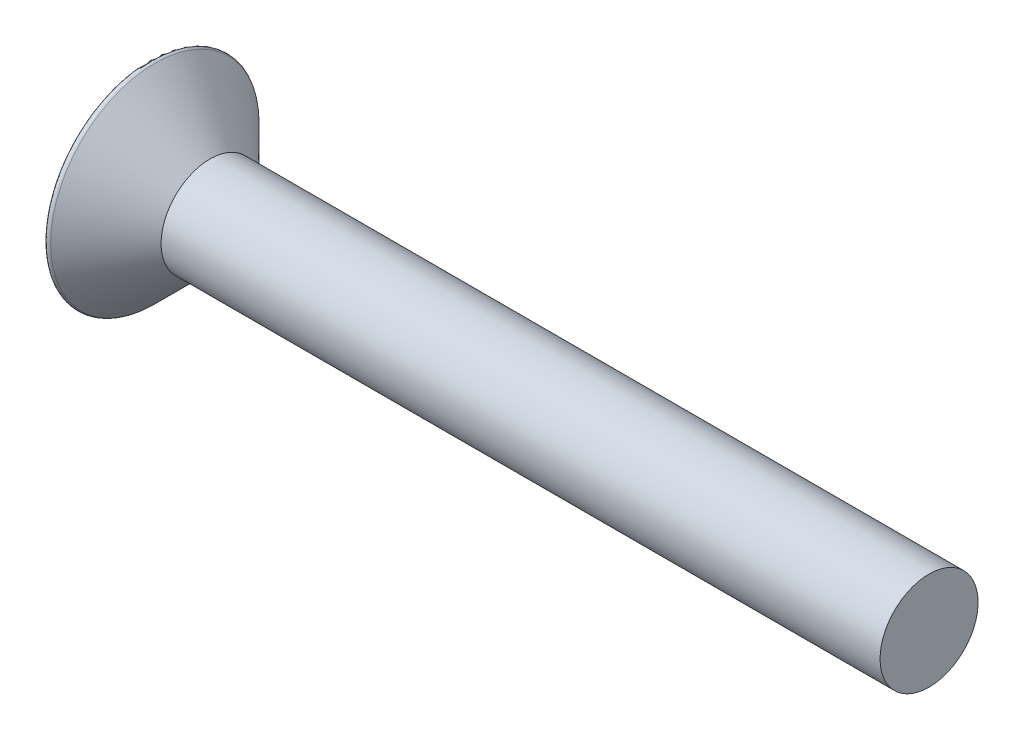
SolidWorks part; units mm, degrees
ref_plane "Plan de face" through (0, 0, 0) normal (0, 0, 1) x (1, 0, 0)
ref_plane "Plan de dessus" through (0, 0, 0) normal (0, 1, 0) x (1, 0, 0)
ref_plane "Plan de droite" through (0, 0, 0) normal (1, 0, 0) x (0, 0, -1)
sketch "Esquisse1" plane through (0, 0, 0) normal (0, 0, 1) x (1, 0, 0)
  line L0 (0, 0) -> (23.86, 0) construction
  line L1 (0, 0) -> (0, 3.36)
  line L2 (0, 3.36) -> (1.86, 1.5)
  line L3 (1.86, 1.5) -> (23.86, 1.5)
  line L4 (23.86, 1.5) -> (23.86, 0)
  line L5 (0, 0) -> (23.86, 0)
  dimension "D1" = 3.36
  dimension "D2" = 1.86
  dimension "D3" = 45
  dimension "D4" = 22
revolve "Révolution1" add sketch "Esquisse1" angle 360 about L0
fillet "Congé1" radius 0.1 1 edges at (0, 0, 3.36)
